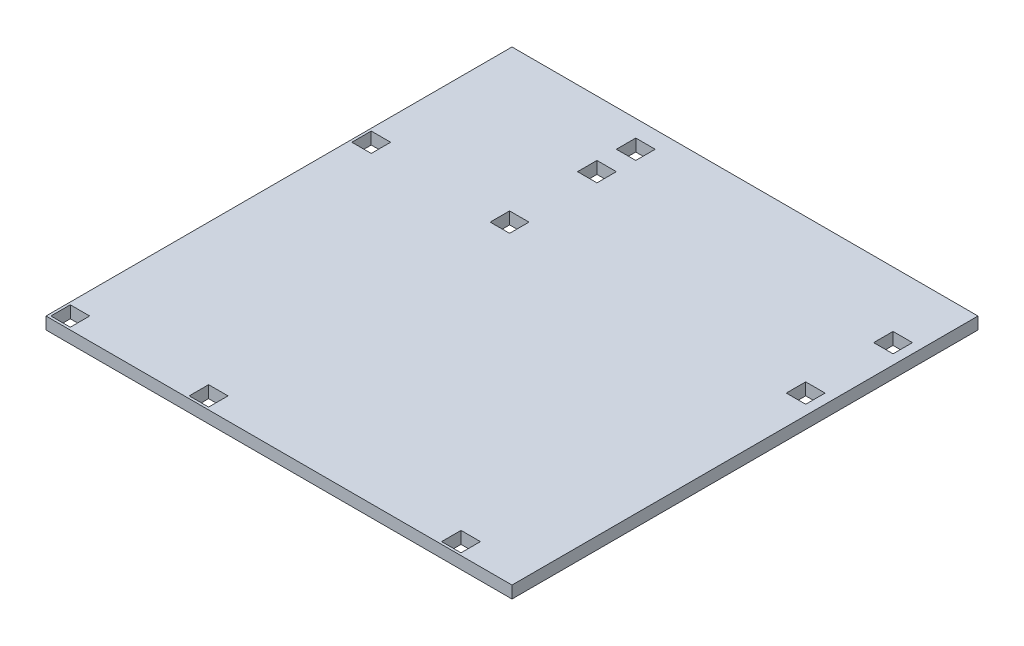
SolidWorks part; units mm, degrees
ref_plane "Front Plane" through (0, 0, 0) normal (0, 0, 1) x (1, 0, 0)
ref_plane "Top Plane" through (0, 0, 0) normal (0, 1, 0) x (1, 0, 0)
ref_plane "Right Plane" through (0, 0, 0) normal (1, 0, 0) x (0, 0, -1)
sketch "Sketch1" plane through (0, 0, 0) normal (0, 1, 0) x (1, 0, 0)
  line L1 (0, 0) -> (243.84, 0)
  line L2 (0, 0) -> (0, 243.84)
  line L3 (0, 243.84) -> (243.84, 243.84)
  line L4 (243.84, 0) -> (243.84, 243.84)
  dimension "D1" = 243.84
  dimension "D2" = 243.84
extrude "Boss-Extrude1" add sketch "Sketch1" along normal blind 6.35 contours L2 L3 L4 L1
sketch "Sketch5" plane through (0, 6.35, 0) normal (0, 1, 0) x (1, 0, 0)
  line L0 (78.74, 229.87) -> (78.74, 209.55) construction
  line L1 (78.74, 209.55) -> (78.74, 163.83) construction
  line L2 (78.74, 163.83) -> (78.74, 6.35) construction
  line L3 (78.74, 6.35) -> (210.82, 6.35) construction
  line L4 (78.74, 6.35) -> (6.35, 6.35) construction
  line L5 (6.35, 6.35) -> (6.35, 163.83) construction
  line L6 (6.35, 163.83) -> (78.74, 163.83) construction
  line L7 (78.74, 163.83) -> (233.68, 163.83) construction
  line L8 (233.68, 163.83) -> (233.68, 209.55) construction
  line L9 (78.74, 209.55) -> (233.68, 209.55) construction
  line L10 (243.84, 0) -> (243.84, 243.84) construction
  line L11 (0, 243.84) -> (243.84, 243.84) construction
  line L13 (1.27, 11.43) -> (11.43, 11.43)
  line L14 (1.27, 11.43) -> (1.27, 1.27)
  line L15 (1.27, 1.27) -> (11.43, 1.27)
  line L16 (11.43, 11.43) -> (11.43, 1.27)
  line L17 (1.27, 11.43) -> (11.43, 1.27) construction
  line L18 (1.27, 1.27) -> (11.43, 11.43) construction
  line L19 (73.66, 11.43) -> (83.82, 11.43)
  line L20 (73.66, 11.43) -> (73.66, 1.27)
  line L21 (73.66, 1.27) -> (83.82, 1.27)
  line L22 (83.82, 11.43) -> (83.82, 1.27)
  line L23 (73.66, 11.43) -> (83.82, 1.27) construction
  line L24 (73.66, 1.27) -> (83.82, 11.43) construction
  line L25 (205.74, 11.43) -> (215.9, 11.43)
  line L26 (205.74, 11.43) -> (205.74, 1.27)
  line L27 (205.74, 1.27) -> (215.9, 1.27)
  line L28 (215.9, 11.43) -> (215.9, 1.27)
  line L29 (205.74, 11.43) -> (215.9, 1.27) construction
  line L30 (205.74, 1.27) -> (215.9, 11.43) construction
  line L31 (228.6, 168.91) -> (238.76, 168.91)
  line L32 (228.6, 168.91) -> (228.6, 158.75)
  line L33 (228.6, 158.75) -> (238.76, 158.75)
  line L34 (238.76, 168.91) -> (238.76, 158.75)
  line L35 (228.6, 168.91) -> (238.76, 158.75) construction
  line L36 (228.6, 158.75) -> (238.76, 168.91) construction
  line L37 (228.6, 214.63) -> (238.76, 214.63)
  line L38 (228.6, 214.63) -> (228.6, 204.47)
  line L39 (228.6, 204.47) -> (238.76, 204.47)
  line L40 (238.76, 214.63) -> (238.76, 204.47)
  line L41 (228.6, 214.63) -> (238.76, 204.47) construction
  line L42 (228.6, 204.47) -> (238.76, 214.63) construction
  line L43 (73.66, 214.63) -> (83.82, 214.63)
  line L44 (73.66, 214.63) -> (73.66, 204.47)
  line L45 (73.66, 204.47) -> (83.82, 204.47)
  line L46 (83.82, 214.63) -> (83.82, 204.47)
  line L47 (73.66, 214.63) -> (83.82, 204.47) construction
  line L48 (73.66, 204.47) -> (83.82, 214.63) construction
  line L49 (73.66, 168.91) -> (83.82, 168.91)
  line L50 (73.66, 168.91) -> (73.66, 158.75)
  line L51 (73.66, 158.75) -> (83.82, 158.75)
  line L52 (83.82, 168.91) -> (83.82, 158.75)
  line L53 (73.66, 168.91) -> (83.82, 158.75) construction
  line L54 (73.66, 158.75) -> (83.82, 168.91) construction
  line L55 (1.27, 168.91) -> (11.43, 168.91)
  line L56 (1.27, 168.91) -> (1.27, 158.75)
  line L57 (1.27, 158.75) -> (11.43, 158.75)
  line L58 (11.43, 168.91) -> (11.43, 158.75)
  line L59 (1.27, 168.91) -> (11.43, 158.75) construction
  line L60 (1.27, 158.75) -> (11.43, 168.91) construction
  line L61 (73.66, 234.95) -> (83.82, 234.95)
  line L62 (73.66, 234.95) -> (73.66, 224.79)
  line L63 (73.66, 224.79) -> (83.82, 224.79)
  line L64 (83.82, 234.95) -> (83.82, 224.79)
  line L65 (73.66, 234.95) -> (83.82, 224.79) construction
  line L66 (73.66, 224.79) -> (83.82, 234.95) construction
  point P0 (233.68, 209.55)
  point P2 (210.82, 6.35)
  point P3 (78.74, 6.35)
  point P4 (6.35, 6.35)
  point P5 (6.35, 163.83)
  point P6 (78.74, 163.83)
  point P7 (78.74, 209.55)
  point P8 (78.74, 229.87)
  point P9 (233.68, 163.83)
  dimension "D1" = 10.16
  dimension "D2" = 22.86
  dimension "D3" = 154.94
  dimension "D4" = 227.33
  dimension "D5" = 20.32
  dimension "D6" = 45.72
  dimension "D7" = 203.2
  dimension "D8" = 34.29
  dimension "D9" = 10.16
  dimension "D10" = 10.16
  dimension "D11" = 10.16
  dimension "D12" = 10.16
  dimension "D13" = 10.16
  dimension "D14" = 10.16
  dimension "D15" = 10.16
  dimension "D16" = 10.16
  dimension "D17" = 10.16
  dimension "D18" = 10.16
  dimension "D19" = 10.16
  dimension "D20" = 10.16
  dimension "D21" = 10.16
  dimension "D22" = 10.16
  dimension "D23" = 10.16
  dimension "D24" = 10.16
  dimension "D25" = 10.16
  dimension "D26" = 10.16
extrude "Cut-Extrude1" cut sketch "Sketch5" against normal up to next
